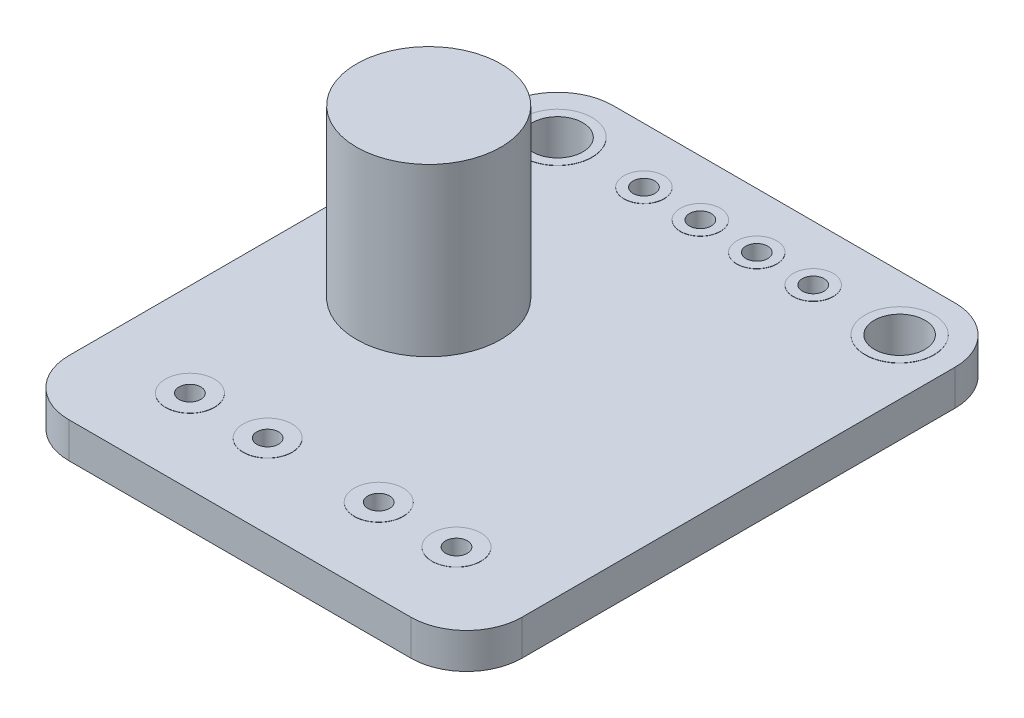
SolidWorks part; units mm, degrees
ref_plane "Front Plane" through (0, 0, 0) normal (0, 0, 1) x (1, 0, 0)
ref_plane "Top Plane" through (0, 0, 0) normal (0, 1, 0) x (1, 0, 0)
ref_plane "Right Plane" through (0, 0, 0) normal (1, 0, 0) x (0, 0, -1)
sketch "Sketch1" plane through (0, 0, 0) normal (0, 1, 0) x (1, 0, 0)
  line L0 (0, 0) -> (0, 12.25) construction
  line L1 (-7.7, 12.25) -> (7.7, 12.25)
  line L2 (-10.2, 9.75) -> (-10.2, -9.75)
  line L3 (-7.7, -12.25) -> (7.7, -12.25)
  line L4 (10.2, 9.75) -> (10.2, -9.75)
  line L5 (-10.2, 12.25) -> (10.2, -12.25) construction
  line L6 (-10.2, -12.25) -> (10.2, 12.25) construction
  arc A0 (-10.2, -9.75) -> (-7.7, -12.25) centre (-7.7, -9.75) ccw
  arc A1 (7.7, -12.25) -> (10.2, -9.75) centre (7.7, -9.75) ccw
  arc A2 (7.7, 12.25) -> (10.2, 9.75) centre (7.7, 9.75) cw
  arc A3 (-7.7, 12.25) -> (-10.2, 9.75) centre (-7.7, 9.75) ccw
  circle A4 centre (-7.7, 9.75) radius 1.15
  circle A5 centre (7.7, 9.75) radius 1.15
  circle A6 centre (-3.81, 9.75) radius 0.5
  circle A7 centre (-1.27, 9.75) radius 0.5
  circle A8 centre (1.27, 9.75) radius 0.5
  circle A9 centre (3.81, 9.75) radius 0.5
  circle A10 centre (-6, -8.5) radius 0.5
  circle A11 centre (-2.5, -8.5) radius 0.5
  circle A12 centre (6, -8.5) radius 0.5
  circle A13 centre (2.5, -8.5) radius 0.5
  point P0 (0, 0)
  dimension "D3" = 2.5
  dimension "D4" = 2.3
  dimension "D5" = 1
  dimension "D12" = 1
  dimension "D1" = 20.4
  dimension "D2" = 24.5
  dimension "D6" = 3.81
  dimension "D8" = 2.54
  dimension "D9" = 3.5
  dimension "D10" = 3.75
  dimension "D11" = 2.5
  dimension "D7" = 4
extrude "Boss-Extrude1" add sketch "Sketch1" along normal blind 1.6
ref_plane "Plane1" through (0, 1.61, 0) normal (0, 1, 0) x (1, 0, 0)
sketch "Sketch2" plane through (0, 1.61, 0) normal (0, 1, 0) x (1, 0, 0)
  circle A0 centre (-6, -8.5) radius 0.5 construction
  circle A1 centre (-2.5, -8.5) radius 0.5 construction
  circle A2 centre (2.5, -8.5) radius 0.5 construction
  circle A3 centre (6, -8.5) radius 0.5 construction
  circle A4 centre (7.7, 9.75) radius 1.15 construction
  circle A5 centre (3.81, 9.75) radius 0.5 construction
  circle A6 centre (1.27, 9.75) radius 0.5 construction
  circle A7 centre (-1.27, 9.75) radius 0.5 construction
  circle A8 centre (-3.81, 9.75) radius 0.5 construction
  circle A9 centre (-7.7, 9.75) radius 1.15 construction
  circle A10 centre (-6, -8.5) radius 0.5 construction
  circle A11 centre (-2.5, -8.5) radius 0.5 construction
  circle A12 centre (2.5, -8.5) radius 0.5 construction
  circle A13 centre (6, -8.5) radius 0.5 construction
  circle A14 centre (7.7, 9.75) radius 1.15 construction
  circle A15 centre (3.81, 9.75) radius 0.5 construction
  circle A16 centre (1.27, 9.75) radius 0.5 construction
  circle A17 centre (-1.27, 9.75) radius 0.5 construction
  circle A18 centre (-3.81, 9.75) radius 0.5 construction
  circle A19 centre (-7.7, 9.75) radius 1.15 construction
  circle A20 centre (7.7, 9.75) radius 1.55
  circle A21 centre (3.81, 9.75) radius 0.9
  circle A22 centre (1.27, 9.75) radius 0.9
  circle A23 centre (-1.27, 9.75) radius 0.9
  circle A24 centre (-3.81, 9.75) radius 0.9
  circle A25 centre (-7.7, 9.75) radius 1.55
  circle A26 centre (-6, -8.5) radius 1.1
  circle A27 centre (-2.5, -8.5) radius 1.1
  circle A28 centre (2.5, -8.5) radius 1.1
  circle A29 centre (6, -8.5) radius 1.1
  circle A30 centre (3.81, 9.75) radius 0.49
  circle A31 centre (1.27, 9.75) radius 0.49
  circle A32 centre (-1.27, 9.75) radius 0.49
  circle A33 centre (-3.81, 9.75) radius 0.49
  circle A34 centre (-7.7, 9.75) radius 1.14
  circle A35 centre (7.7, 9.75) radius 1.14
  circle A36 centre (-6, -8.5) radius 0.49
  circle A37 centre (-2.5, -8.5) radius 0.49
  circle A38 centre (2.5, -8.5) radius 0.49
  circle A39 centre (6, -8.5) radius 0.49
  dimension "D1" = 0.4
  dimension "D2" = 0.6
  dimension "D3" = 0.01
extrude "Boss-Extrude2" add sketch "Sketch2" against normal offset from surface (1.62 mm away) 0.01 up to face at (0, 0, 0) offset beyond the face yes
sketch "Sketch3" plane through (0, 1.6, 0) normal (0, 1, 0) x (1, 0, 0)
  line L0 (-10.2, 9.75) -> (-10.2, -9.75) construction
  line L2 (7.7, 12.25) -> (-7.7, 12.25) construction
  circle A0 centre (-4.3504, 0.6) radius 3.25
  point P4 (0, 0)
  point P6 (-5.7579, 12.25)
  dimension "D1" = 6.5
  dimension "D2" = 5.8496
  dimension "D3" = 11.65
extrude "Boss-Extrude3" add sketch "Sketch3" along normal blind 7.5
